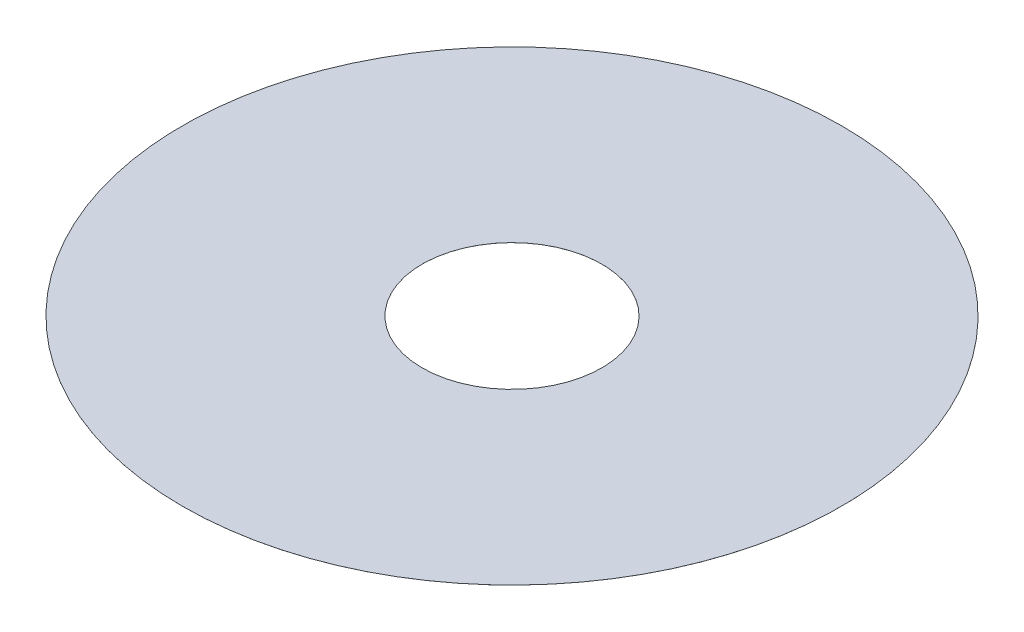
SolidWorks part; units mm, degrees
ref_plane "Front Plane" through (0, 0, 0) normal (0, 0, 1) x (1, 0, 0)
ref_plane "Top Plane" through (0, 0, 0) normal (0, 1, 0) x (1, 0, 0)
ref_plane "Right Plane" through (0, 0, 0) normal (1, 0, 0) x (0, 0, -1)
sketch "Sketch1" plane through (0, 0, 0) normal (0, 1, 0) x (1, 0, 0)
  circle A0 centre (0, 0) radius 22000
  circle A1 centre (0, 0) radius 6000
  dimension "D1" = 44000
  dimension "D2" = 12000
extrude "Boss-Extrude1" add sketch "Sketch1" along normal blind 1.5875
